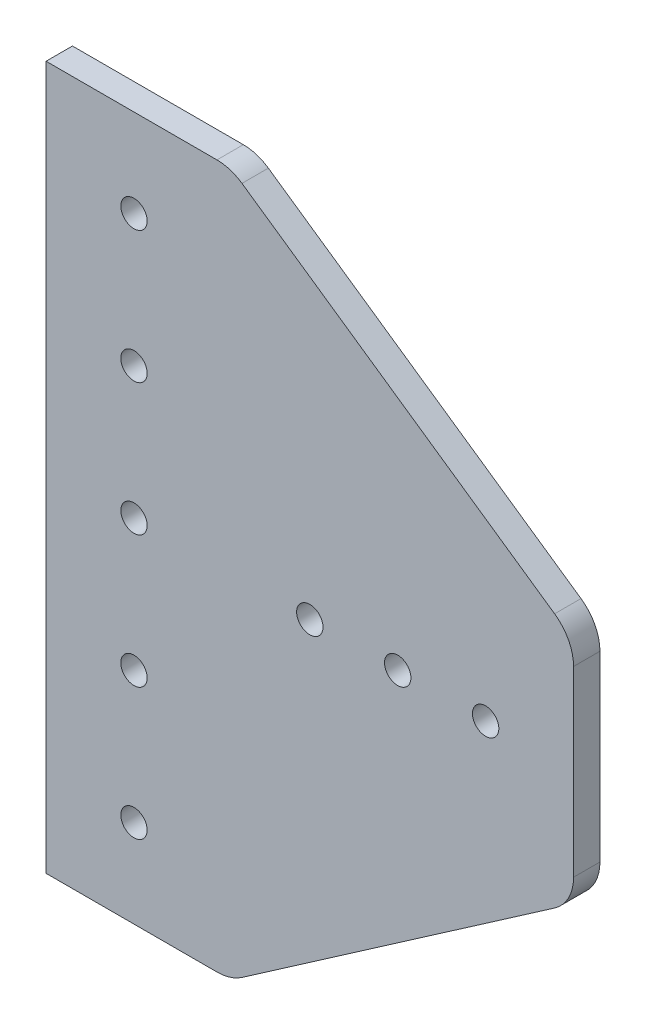
SolidWorks part; units mm, degrees
ref_plane "前视基准面" through (0, 0, 0) normal (0, 0, 1) x (1, 0, 0)
ref_plane "上视基准面" through (0, 0, 0) normal (0, 1, 0) x (1, 0, 0)
ref_plane "右视基准面" through (0, 0, 0) normal (1, 0, 0) x (0, 0, -1)
sketch "草图1" plane through (0, 0, 0) normal (0, 0, 1) x (1, 0, 0)
  line L0 (0, 40) -> (0, -40)
  line L1 (0, 40) -> (21, 40)
  line L2 (21, -40) -> (0, -40)
  line L3 (0, 0) -> (60, 0) construction
  line L4 (60, 13) -> (60, -13)
  line L5 (60, 13) -> (21, 40)
  line L6 (60, -13) -> (21, -40)
  line L7 (10, -40) -> (10, 40) construction
  line L8 (20, -40) -> (20, 40) construction
  circle A0 centre (10, 0) radius 1.5
  circle A1 centre (10, 15) radius 1.5
  circle A2 centre (10, 30) radius 1.5
  circle A3 centre (10, -15) radius 1.5
  circle A4 centre (10, -30) radius 1.5
  circle A5 centre (30, 0) radius 1.5
  circle A6 centre (40, 0) radius 1.5
  circle A7 centre (50, 0) radius 1.5
  point P3 (0, 0)
  point P9 (60, 0)
  dimension "D7" = 3
  dimension "D8" = 3
  dimension "D9" = 3
  dimension "D12" = 10
  dimension "D13" = 3
  dimension "D15" = 3
  dimension "D16" = 3
  dimension "D17" = 10
  dimension "D1" = 80
  dimension "D2" = 26
  dimension "D3" = 60
  dimension "D4" = 21
  dimension "D5" = 10
  dimension "D6" = 20
  dimension "D10" = 15
  dimension "D11" = 15
  dimension "D14" = 10
extrude "凸台-拉伸1" add sketch "草图1" along normal mid plane 3
fillet "圆角1" radius 5 4 edges at (21, 40, 0) (21, -40, 0) (60, -13, 0) (60, 13, 0)
